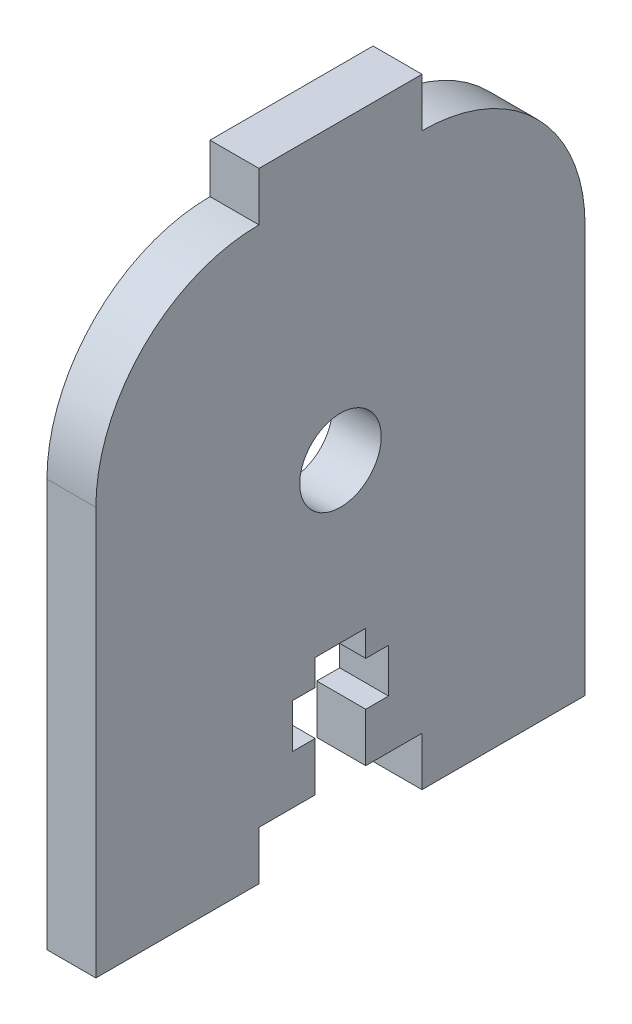
SolidWorks part; units mm, degrees
ref_plane "Front Plane" through (0, 0, 0) normal (0, 0, 1) x (1, 0, 0)
ref_plane "Top Plane" through (0, 0, 0) normal (0, 1, 0) x (1, 0, 0)
ref_plane "Right Plane" through (0, 0, 0) normal (1, 0, 0) x (0, 0, -1)
sketch "Sketch1" plane through (0, 0, 0) normal (1, 0, 0) x (0, 0, -1)
  line L1 (0, 0) -> (30, 0)
  line L2 (0, 0) -> (0, 35)
  line L3 (0, 35) -> (30, 35)
  line L4 (30, 0) -> (30, 35)
  dimension "D1" = 30
  dimension "D2" = 35
extrude "Boss-Extrude1" add sketch "Sketch1" along normal blind 3
fillet "Fillet1" radius 10 2 edges at (1.5, 35, -30) (1.5, 35, 0)
sketch "Sketch2" plane through (3, 0, 0) normal (1, 0, 0) x (0, 0, -1)
  line L0 (0, 0) -> (30, 0) construction
  line L1 (10, 0) -> (20, 0)
  line L2 (10, 0) -> (10, 3)
  line L3 (10, 3) -> (20, 3)
  line L4 (20, 0) -> (20, 3)
  line L5 (0, 25) -> (0, 0) construction
  dimension "D1" = 10
  dimension "D2" = 10
  dimension "D3" = 3
extrude "Cut-Extrude1" cut sketch "Sketch2" against normal blind 3
hole_wizard "Ø5.0mm Dowel Hole1" positions "Sketch3" profile "Sketch4" hole size "Ø5.0" standard "ANSI Metric"
sketch "Sketch3" plane through (3, 0, 0) normal (1, 0, 0) x (0, 0, -1)
  line L0 (0, 25) -> (0, 0) construction
  line L1 (0, 0) -> (10, 0) construction
  point P0 (15, 20)
  dimension "D1" = 15
  dimension "D2" = 20
sketch "Sketch4" plane through (3, 20, -15) normal (0, 1, 0) x (0, 0, -1)
  line L0 (0, 0) -> (0, 4.5022)
  line L1 (0, 4.5022) -> (2.5, 3)
  line L2 (2.5, 3) -> (2.5, 0)
  line L5 (2.5, 0) -> (0, 0)
  line L10 (0, 4.5022) -> (-2.5, 3) construction
  line L11 (0, -6.35) -> (0, 107.95) construction
  dimension "Hole Dia." = 5
  dimension "Hole Depth" = 3
  dimension "Drill Angle" = 118
sketch "Sketch5" plane through (3, 0, 0) normal (1, 0, 0) x (0, 0, -1)
  line L0 (13.45, 3) -> (13.45, 6)
  line L1 (20, 3) -> (10, 3) construction
  line L2 (13.45, 6) -> (12.05, 6)
  line L3 (12.05, 6) -> (12.05, 8.7)
  line L4 (12.05, 8.7) -> (13.45, 8.7)
  line L5 (13.45, 8.7) -> (13.45, 10.3)
  line L6 (13.45, 10.3) -> (16.55, 10.3)
  line L7 (16.55, 10.3) -> (16.55, 8.7)
  line L8 (16.55, 8.7) -> (17.95, 8.7)
  line L9 (17.95, 8.7) -> (17.95, 6)
  line L10 (17.95, 6) -> (16.55, 6)
  line L11 (16.55, 6) -> (16.55, 3)
  line L12 (16.55, 3) -> (13.45, 3)
  line L13 (10, 3) -> (10, 0) construction
  line L14 (0, 0) -> (10, 0) construction
  dimension "D1" = 3.1
  dimension "D2" = 3.45
  dimension "D3" = 2.7
  dimension "D4" = 3
  dimension "D5" = 10.3
  dimension "D6" = 5.9
extrude "Cut-Extrude2" cut sketch "Sketch5" against normal blind 3
sketch "Sketch6" plane through (0, 35, 0) normal (0, 1, 0) x (1, 0, 0)
  line L1 (3, 10) -> (0, 10)
  line L2 (3, 10) -> (3, 20)
  line L3 (3, 20) -> (0, 20)
  line L4 (0, 10) -> (0, 20)
extrude "Boss-Extrude2" add sketch "Sketch6" along normal blind 3
